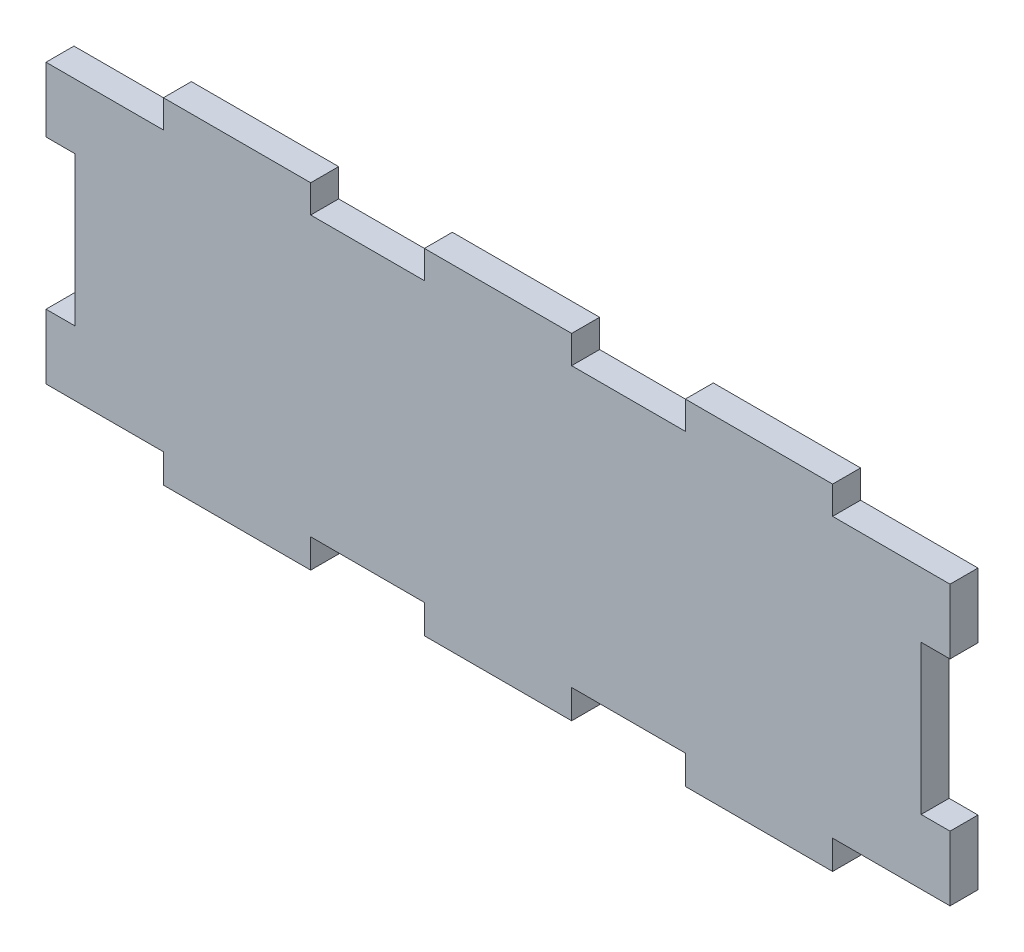
SolidWorks part; units mm, degrees
ref_plane "Front Plane" through (0, 0, 0) normal (0, 0, 1) x (1, 0, 0)
ref_plane "Top Plane" through (0, 0, 0) normal (0, 1, 0) x (1, 0, 0)
ref_plane "Right Plane" through (0, 0, 0) normal (1, 0, 0) x (0, 0, -1)
sketch "Sketch1" plane through (0, 0, 0) normal (0, 0, 1) x (1, 0, 0)
  line L0 (0, 29.9) -> (12.6, 29.9)
  line L1 (12.6, -3.1) -> (28.4, -3.1)
  line L2 (0, 0) -> (0, 6.95)
  line L3 (12.6, 32.9) -> (28.4, 32.9)
  line L4 (97, 0) -> (97, 6.95)
  line L5 (68.6, 32.9) -> (84.4, 32.9)
  line L6 (40.6, 32.9) -> (56.4, 32.9)
  line L7 (12.6, 29.9) -> (12.6, 32.9)
  line L8 (12.6, 32.9) -> (28.4, 32.9)
  line L9 (28.4, 32.9) -> (28.4, 29.9)
  line L10 (28.4, 29.9) -> (40.6, 29.9)
  line L11 (40.6, 29.9) -> (40.6, 32.9)
  line L12 (40.6, 32.9) -> (56.4, 32.9)
  line L13 (56.4, 32.9) -> (56.4, 29.9)
  line L14 (56.4, 29.9) -> (68.6, 29.9)
  line L15 (68.6, 29.9) -> (68.6, 32.9)
  line L16 (68.6, 32.9) -> (84.4, 32.9)
  line L17 (84.4, 32.9) -> (84.4, 29.9)
  line L18 (84.4, 29.9) -> (97, 29.9)
  line L19 (0, 22.95) -> (3.1, 22.95)
  line L20 (3.1, 22.95) -> (3.1, 6.95)
  line L21 (3.1, 6.95) -> (0, 6.95)
  line L22 (0, 0) -> (12.6, 0)
  line L23 (12.6, 0) -> (12.6, -3.1)
  line L24 (12.6, -3.1) -> (28.4, -3.1)
  line L25 (28.4, -3.1) -> (28.4, 0)
  line L26 (28.4, 0) -> (40.6, 0)
  line L27 (40.6, 0) -> (40.6, -3.1)
  line L28 (40.6, -3.1) -> (56.4, -3.1)
  line L29 (56.4, -3.1) -> (56.4, 0)
  line L30 (56.4, 0) -> (68.6, 0)
  line L31 (68.6, 0) -> (68.6, -3.1)
  line L32 (68.6, -3.1) -> (84.4, -3.1)
  line L33 (84.4, -3.1) -> (84.4, 0)
  line L34 (84.4, 0) -> (97, 0)
  line L35 (40.6, -3.1) -> (56.4, -3.1)
  line L36 (68.6, -3.1) -> (84.4, -3.1)
  line L37 (97, 22.95) -> (93.9, 22.95)
  line L38 (93.9, 22.95) -> (93.9, 6.95)
  line L39 (93.9, 6.95) -> (97, 6.95)
  line L40 (0, 22.95) -> (0, 29.9)
  line L41 (97, 22.95) -> (97, 29.9)
  point P0 (0, 0)
  point P24 (0, 0)
  point P39 (-35.0489, -13.8403)
  point P40 (0, 0)
  point P41 (0, 0)
  point P42 (0, 0)
  point P43 (50.8255, 15.2249)
  point P44 (34.8066, 15.0598)
  point P45 (47.6052, -10.5374)
  point P46 (34.9718, -10.62)
  point P47 (21.7603, -10.3723)
  point P48 (22.586, 15.7204)
  point P49 (20.1634, 20.0983)
  point P50 (20.9792, -11.067)
  point P51 (6.9467, 18.3034)
  point P52 (0, 0)
  point P53 (103, 0)
  point P54 (103, 6.298)
  point P55 (43.7282, 0)
  point P56 (5.0522, 20.8478)
  point P57 (0, 22.1194)
  dimension "D1" = 36
  dimension "D2" = 97
  dimension "D3" = 15.8
  dimension "D4" = 12.2
  dimension "D5" = 3
  dimension "D6" = 16
  dimension "D7" = 3.1
extrude "Boss-Extrude1" add sketch "Sketch1" along normal blind 3 contours L37 L41 L18 L17 L5 L15 L14 L13 L6 L11 L10 L9 L3 L7 L0 L40 L19 L20 L21 L2 L22 L23 L1 L25 L26 L27 L28 L29 L30 L31 L32 L33 L34 L4 L39 L38
